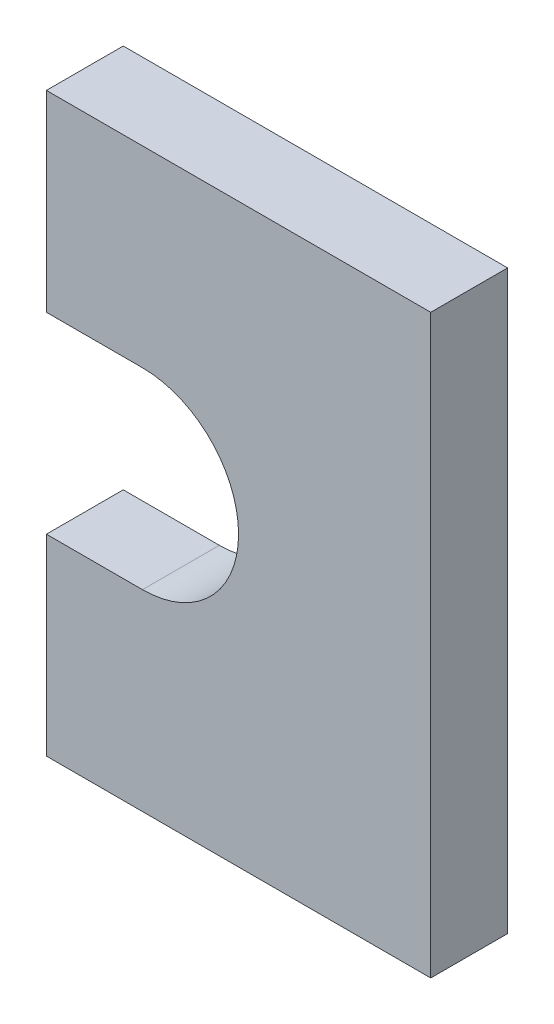
SolidWorks part; units mm, degrees
ref_plane "Front Plane" through (0, 0, 0) normal (0, 0, 1) x (1, 0, 0)
ref_plane "Top Plane" through (0, 0, 0) normal (0, 1, 0) x (1, 0, 0)
ref_plane "Right Plane" through (0, 0, 0) normal (1, 0, 0) x (0, 0, -1)
sketch "Sketch1" plane through (0, 0, 0) normal (0, 0, 1) x (1, 0, 0)
  line L0 (-5, 2.5) -> (-5, 7.5)
  line L1 (-5, -7.5) -> (5, -7.5)
  line L2 (-5, -7.5) -> (-5, -2.5)
  line L3 (-5, 7.5) -> (5, 7.5)
  line L4 (5, -7.5) -> (5, 7.5)
  line L5 (-5, -7.5) -> (5, 7.5) construction
  line L6 (-5, 7.5) -> (5, -7.5) construction
  line L7 (-5, 2.5) -> (-2.5, 2.5)
  line L9 (-5, -2.5) -> (-2.5, -2.5)
  arc A0 (-2.5, 2.5) -> (-2.5, -2.5) centre (-2.5, 0) cw
  point P0 (0, 0)
  dimension "D1" = 15
  dimension "D2" = 10
  dimension "D3" = 5
  dimension "D4" = 2.5
  dimension "D5" = 2.5
extrude "Boss-Extrude1" add sketch "Sketch1" along normal blind 2
